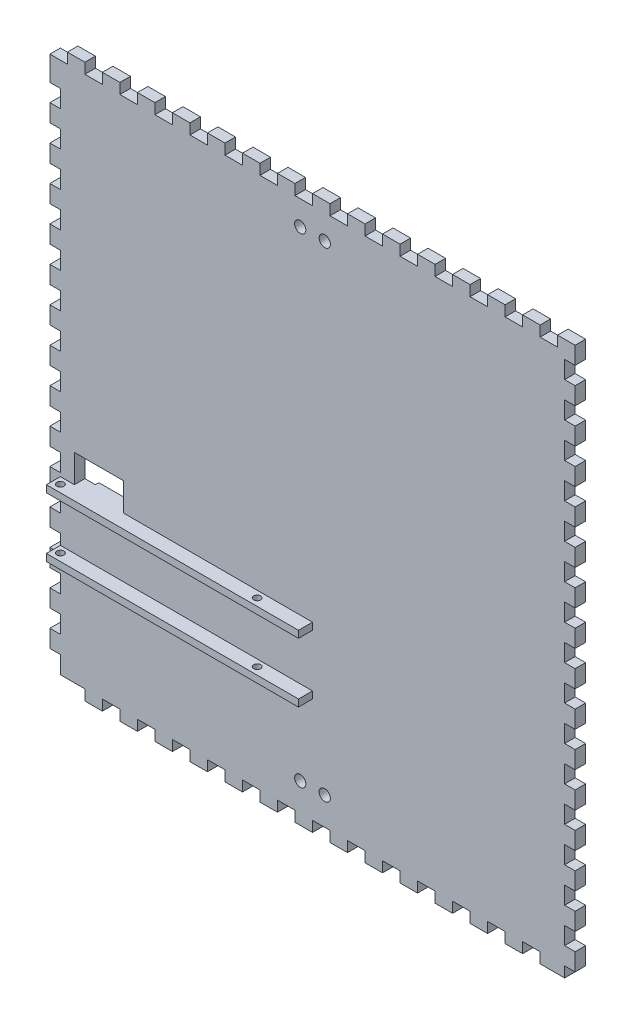
SolidWorks part; units mm, degrees
ref_plane "Front Plane" through (0, 0, 0) normal (0, 0, 1) x (1, 0, 0)
ref_plane "Top Plane" through (0, 0, 0) normal (0, 1, 0) x (1, 0, 0)
ref_plane "Right Plane" through (0, 0, 0) normal (1, 0, 0) x (0, 0, -1)
sketch "Sketch1" plane through (0, 0, 0) normal (0, 0, 1) x (1, 0, 0)
  line L1 (-75, 79) -> (75, 79)
  line L2 (-75, 79) -> (-75, -79)
  line L3 (-75, -79) -> (75, -79)
  line L4 (75, 79) -> (75, -79)
  line L5 (-75, 79) -> (75, -79) construction
  line L6 (-75, -79) -> (75, 79) construction
  point P0 (0, 0)
  dimension "D1" = 158
  dimension "D2" = 150
extrude "Boss-Extrude1" add sketch "Sketch1" along normal blind 5
sketch "Sketch2" plane through (0, 0, 0) normal (0, 0, -1) x (-1, 0, 0)
  line L1 (-65, 65) -> (65, 65)
  line L2 (-65, 65) -> (-65, -65)
  line L3 (-65, -65) -> (65, -65)
  line L4 (65, 65) -> (65, -65)
  line L5 (-65, 65) -> (65, -65) construction
  line L6 (-65, -65) -> (65, 65) construction
  line L7 (-75, 79) -> (75, 79)
  line L8 (-75, 79) -> (-75, -79)
  line L9 (-75, -79) -> (75, -79)
  line L10 (75, 79) -> (75, -79)
  line L11 (-75, 79) -> (75, -79) construction
  line L12 (-75, -79) -> (75, 79) construction
  point P0 (0, 0)
  point P6 (0, 0)
  dimension "D1" = 130
  dimension "D2" = 130
extrude "Cut-Extrude1" cut sketch "Sketch2" against normal blind 2
sketch "Sketch3" plane through (0, 0, 0) normal (0, 0, -1) x (-1, 0, 0)
  line L1 (-65, 65) -> (-65, -65) construction
  line L2 (-65, 51.95) -> (-55, 51.95)
  line L3 (-65, 51.95) -> (-65, 38.85)
  line L4 (-65, 38.85) -> (-55, 38.85)
  line L5 (-55, 51.95) -> (-55, 38.85)
  dimension "D1" = 13.1
  dimension "D2" = 10
  dimension "D3" = 13.05
extrude "Cut-Extrude2" cut sketch "Sketch3" against normal blind 1
pattern_linear "LPattern1" count 7 spacing 20 along (-1, 0, 0) count 5 spacing 26 along (0, -1, 0) of "Cut-Extrude2"
sketch "Sketch4" plane through (0, 0, 0) normal (0, 0, -1) x (-1, 0, 0)
  line L0 (65, 65) -> (-65, 65) construction
  line L1 (-55, 65) -> (-45, 65)
  line L2 (-55, 65) -> (-55, 51.9)
  line L3 (-55, 51.9) -> (-45, 51.9)
  line L4 (-45, 65) -> (-45, 51.9)
  dimension "D1" = 13.1
  dimension "D2" = 10
  dimension "D3" = 10
extrude "Cut-Extrude3" cut sketch "Sketch4" against normal blind 1
pattern_linear "LPattern2" count 6 spacing 20 along (-1, 0, 0) count 5 spacing 26 along (0, -1, 0) of "Cut-Extrude3"
sketch "Sketch5" plane through (0, 0, 2) normal (0, 0, -1) x (-1, 0, 0)
  line L0 (75, 79) -> (-75, 79) construction
  line L1 (-70, 79) -> (-65, 79)
  line L2 (-70, 79) -> (-70, 76)
  line L3 (-70, 76) -> (-65, 76)
  line L4 (-65, 79) -> (-65, 76)
  dimension "D1" = 5
  dimension "D2" = 5
  dimension "D3" = 3
extrude "Cut-Extrude4" cut sketch "Sketch5" against normal through all
pattern_linear "LPattern3" count 15 spacing 10 along (-1, 0, 0) of "Cut-Extrude4"
sketch "Sketch6" plane through (0, 0, 2) normal (0, 0, -1) x (-1, 0, 0)
  line L0 (-75, 79) -> (-75, -79) construction
  line L1 (-75, 74) -> (-72, 74)
  line L2 (-75, 74) -> (-75, 69)
  line L3 (-75, 69) -> (-72, 69)
  line L4 (-72, 74) -> (-72, 69)
  dimension "D1" = 3
  dimension "D2" = 5
  dimension "D3" = 5
extrude "Cut-Extrude5" cut sketch "Sketch6" against normal through all
pattern_linear "LPattern4" count 16 spacing 10 along (0, -1, 0) of "Cut-Extrude5"
sketch "Sketch7" plane through (0, 0, 2) normal (0, 0, -1) x (-1, 0, 0)
  line L0 (75, -79) -> (75, 76) construction
  line L1 (75, 69) -> (72, 69)
  line L2 (75, 69) -> (75, 64)
  line L3 (75, 64) -> (72, 64)
  line L4 (72, 69) -> (72, 64)
  dimension "D1" = 5
  dimension "D2" = 3
  dimension "D3" = 10
extrude "Cut-Extrude6" cut sketch "Sketch7" against normal through all
pattern_linear "LPattern5" count 15 spacing 10 along (0, -1, 0) of "Cut-Extrude6"
sketch "Sketch8" plane through (0, 0, 2) normal (0, 0, -1) x (-1, 0, 0)
  line L0 (-72, -79) -> (75, -79) construction
  line L1 (-65, -79) -> (-60, -79)
  line L2 (-65, -79) -> (-65, -76)
  line L3 (-65, -76) -> (-60, -76)
  line L4 (-60, -79) -> (-60, -76)
  dimension "D1" = 3
  dimension "D2" = 5
  dimension "D3" = 10
extrude "Cut-Extrude7" cut sketch "Sketch8" against normal through all
pattern_linear "LPattern6" count 14 spacing 10 along (-1, 0, 0) of "Cut-Extrude7"
sketch "Sketch9" plane through (0, 0, 2) normal (0, 0, -1) x (-1, 0, 0)
  line L1 (75, -79) -> (70, -79)
  line L2 (75, -79) -> (75, -76)
  line L3 (75, -76) -> (70, -76)
  line L4 (70, -79) -> (70, -76)
extrude "Cut-Extrude8" cut sketch "Sketch9" against normal blind 3
sketch "Sketch10" plane through (0, 0, 2) normal (0, 0, -1) x (-1, 0, 0)
  line L0 (-10, 76) -> (-5, 76) construction
  line L1 (0, 76) -> (5, 76) construction
  circle A0 centre (3.5, 69) radius 1.6
  circle A1 centre (-3.5, 69) radius 1.6
  dimension "D1" = 3.2
  dimension "D2" = 3.2
  dimension "D3" = 3.5
  dimension "D4" = 3.5
  dimension "D5" = 7
  dimension "D6" = 7
extrude "Cut-Extrude9" cut sketch "Sketch10" against normal blind 10
sketch "Sketch11" plane through (0, 0, 2) normal (0, 0, -1) x (-1, 0, 0)
  line L0 (0, -76) -> (-5, -76) construction
  circle A0 centre (3.5, -68) radius 1.6
  circle A1 centre (-3.5, -68) radius 1.6
  dimension "D1" = 3.2
  dimension "D2" = 3.2
  dimension "D3" = 3.5
  dimension "D4" = 3.5
  dimension "D5" = 8
  dimension "D6" = 8
extrude "Cut-Extrude10" cut sketch "Sketch11" against normal blind 10
sketch "Sketch12" plane through (0, 0, 0) normal (1, 0, 0) x (0, 0, -1)
  line L0 (-5, -46) -> (-5, -41) construction
  line L1 (-5, -46) -> (-9, -46)
  line L2 (-5, -46) -> (-5, -44)
  line L3 (-5, -44) -> (-9, -44)
  line L4 (-9, -46) -> (-9, -44)
  line L5 (-5, -46) -> (-2, -46) construction
  point P6 (0, 0)
  dimension "D1" = 2
  dimension "D2" = 4
extrude "Boss-Extrude2" add sketch "Sketch12" against normal up to surface (72 mm away) up to face at (-72, -43.5, 3.5)
sketch "Sketch13" plane through (0, -44, 0) normal (0, 1, 0) x (1, 0, 0)
  line L0 (-72, -9) -> (-72, -5) construction
  line L1 (-72, -5) -> (0, -5) construction
  line L2 (-12, -22.3757) -> (-12, 5.8449) construction
  circle A0 centre (-70.1, -6.9) radius 1
  circle A1 centre (-13.9, -6.9) radius 1
  dimension "D1" = 2
  dimension "D5" = 2
  dimension "D2" = 1.9
  dimension "D3" = 1.9
  dimension "D4" = 60
  dimension "D6" = 1.9
  dimension "D7" = 1.9
extrude "Cut-Extrude11" cut sketch "Sketch13" against normal blind 10
sketch "Sketch14" plane through (0, 0, 0) normal (1, 0, 0) x (0, 0, -1)
  line L0 (-5, -26) -> (-5, -21) construction
  line L1 (-5, -27) -> (-9, -27)
  line L2 (-5, -27) -> (-5, -29)
  line L3 (-5, -29) -> (-9, -29)
  line L4 (-9, -27) -> (-9, -29)
  line L5 (-5, -44) -> (-9, -44) construction
  dimension "D1" = 2
  dimension "D2" = 4
  dimension "D3" = 15
extrude "Boss-Extrude3" add sketch "Sketch14" against normal up to surface (72 mm away) up to face at (-72, -33.5, 3.5)
sketch "Sketch15" plane through (0, -27, 0) normal (0, 1, 0) x (1, 0, 0)
  circle A0 centre (-70.1, -6.9) radius 1 construction
  circle A1 centre (-13.9, -6.9) radius 1 construction
  circle A2 centre (-70.1, -6.9) radius 1
  circle A3 centre (-13.9, -6.9) radius 1
extrude "Cut-Extrude12" cut sketch "Sketch15" against normal through all
sketch "Sketch16" plane through (0, 0, 5) normal (0, 0, 1) x (1, 0, 0)
  line L0 (-72, -27) -> (0, -27) construction
  line L1 (-54, -27) -> (-68, -27)
  line L2 (-54, -27) -> (-54, -19)
  line L3 (-54, -19) -> (-68, -19)
  line L4 (-68, -27) -> (-68, -19)
  line L5 (-72, -29) -> (-72, -27) construction
  dimension "D1" = 4
  dimension "D2" = 14
  dimension "D3" = 8
extrude "Cut-Extrude13" cut sketch "Sketch16" against normal through all
